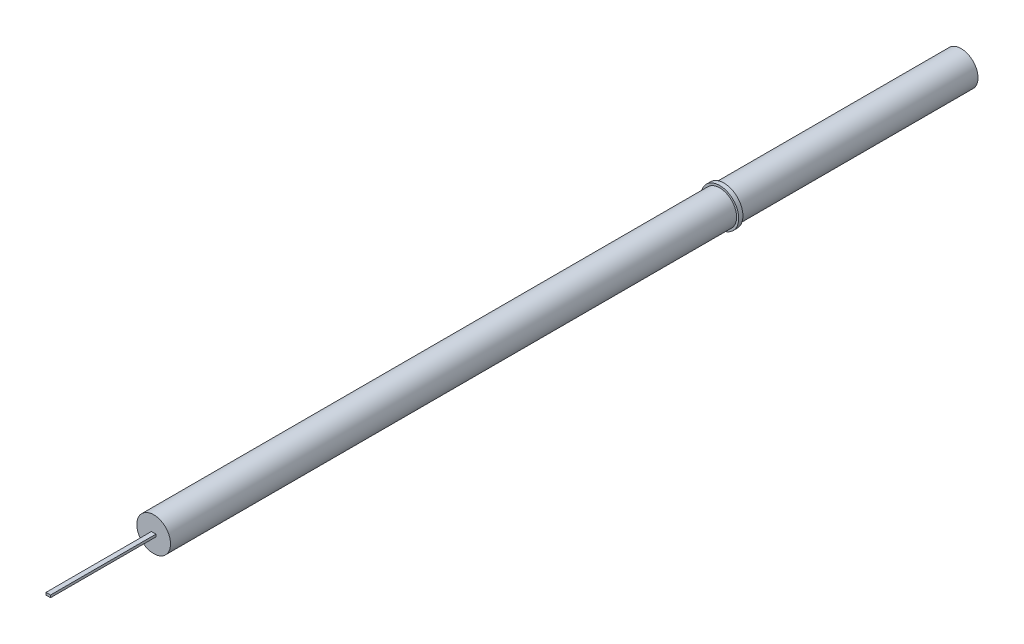
SolidWorks part; units mm, degrees
ref_plane "Front Plane" through (0, 0, 0) normal (0, 0, 1) x (1, 0, 0)
ref_plane "Top Plane" through (0, 0, 0) normal (0, 1, 0) x (1, 0, 0)
ref_plane "Right Plane" through (0, 0, 0) normal (1, 0, 0) x (0, 0, -1)
sketch "Sketch4" plane through (0, 0, 0) normal (0, 0, 1) x (1, 0, 0)
  circle A0 centre (0, 0) radius 0.8
  dimension "D1" = 1.6
extrude "Boss-Extrude2" add sketch "Sketch4" along normal blind 38.3
sketch "Sketch5" plane through (0, 0, 0) normal (1, 0, 0) x (0, 0, -1)
  line L0 (-38.3, 0.8) -> (-11.45, 0.8) construction
  line L1 (0, 0.8) -> (-38.3, 0.8) construction
  dimension "D1" = 26.85
ref_plane "Plane1" through (0, 0, 11.45) normal (0, 0, -1) x (-1, 0, 0)
sketch "Sketch6" plane through (0, 0, 11.45) normal (0, 0, -1) x (-1, 0, 0)
  circle A0 centre (0, 0) radius 0.9
  dimension "D1" = 1.8
extrude "Boss-Extrude3" add sketch "Sketch6" along normal blind 0.2
sketch "Sketch7" plane through (0, 0, 0) normal (0, 0, -1) x (-1, 0, 0)
  circle A0 centre (0, 0) radius 0.75
  dimension "D1" = 1.5
extrude "Cut-Extrude1" cut sketch "Sketch7" against normal blind 38.25
sketch "Sketch8" plane through (0, 0, 38.3) normal (0, 0, 1) x (1, 0, 0)
  line L1 (-0.1077, -0.057) -> (0.1077, -0.057)
  line L2 (-0.1077, -0.057) -> (-0.1077, 0.057)
  line L3 (-0.1077, 0.057) -> (0.1077, 0.057)
  line L4 (0.1077, -0.057) -> (0.1077, 0.057)
  line L5 (-0.1077, -0.057) -> (0.1077, 0.057) construction
  line L6 (-0.1077, 0.057) -> (0.1077, -0.057) construction
  point P0 (0, 0)
extrude "Boss-Extrude4" add sketch "Sketch8" along normal blind 5
